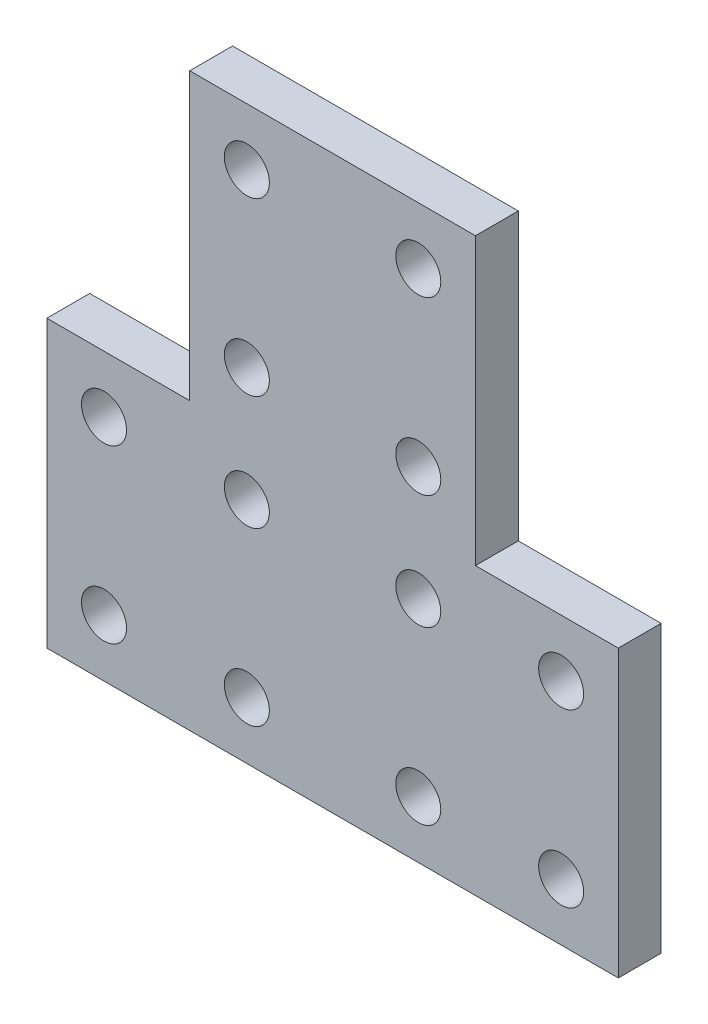
SolidWorks part; units mm, degrees
material "Thornel VCB-20 碳布"
ref_plane "前视基准面" through (0, 0, 0) normal (0, 0, 1) x (1, 0, 0)
ref_plane "上视基准面" through (0, 0, 0) normal (0, 1, 0) x (1, 0, 0)
ref_plane "右视基准面" through (0, 0, 0) normal (1, 0, 0) x (0, 0, -1)
other "Configuration Table"
sketch "草图1" plane through (0, 0, 0) normal (0, 0, 1) x (1, 0, 0)
  line L0 (0, 0) -> (40, 0)
  line L1 (40, 0) -> (40, 20)
  line L2 (40, 20) -> (30, 20)
  line L3 (30, 20) -> (30, 40)
  line L4 (30, 40) -> (10, 40)
  line L5 (10, 40) -> (10, 20)
  line L6 (10, 20) -> (0, 20)
  line L7 (0, 20) -> (0, 0)
  dimension "D1" = 20
  dimension "D2" = 20
  dimension "D3" = 20
  dimension "D4" = 10
extrude "凸台-拉伸1" add sketch "草图1" along normal blind 3
sketch "草图2" plane through (0, 0, 3) normal (0, 0, 1) x (1, 0, 0)
  line L0 (10, 40) -> (10, 20) construction
  line L1 (14, 36) -> (26, 36) construction
  line L2 (14, 36) -> (14, 24) construction
  line L3 (14, 24) -> (26, 24) construction
  line L4 (26, 36) -> (26, 24) construction
  line L5 (30, 40) -> (10, 40) construction
  line L6 (40, 20) -> (30, 20) construction
  line L7 (0, 20) -> (0, 0) construction
  line L8 (4, 16) -> (36, 16) construction
  line L9 (4, 16) -> (4, 4) construction
  line L10 (4, 4) -> (36, 4) construction
  line L11 (36, 16) -> (36, 4) construction
  line L12 (10, 20) -> (0, 20) construction
  line L13 (40, 0) -> (40, 20) construction
  line L14 (0, 0) -> (40, 0) construction
  circle A0 centre (14, 36) radius 1.575
  circle A1 centre (26, 36) radius 1.575
  circle A2 centre (26, 24) radius 1.575
  circle A3 centre (14, 24) radius 1.575
  circle A4 centre (4, 16) radius 1.575
  circle A5 centre (4, 4) radius 1.575
  circle A6 centre (14, 16) radius 1.575
  circle A7 centre (14, 4) radius 1.575
  circle A8 centre (36, 16) radius 1.575
  circle A9 centre (36, 4) radius 1.575
  circle A10 centre (26, 4) radius 1.575
  circle A11 centre (26, 16) radius 1.575
  dimension "D5" = 3.15
  dimension "D10" = 3.15
  dimension "D1" = 12
  dimension "D2" = 4
  dimension "D3" = 4
  dimension "D4" = 4
  dimension "D6" = 4
  dimension "D7" = 4
  dimension "D8" = 4
  dimension "D9" = 4
  dimension "D11" = 10
  dimension "D12" = 10
  dimension "D13" = 10
  dimension "D14" = 10
extrude "切除-拉伸1" cut sketch "草图2" against normal blind 3
